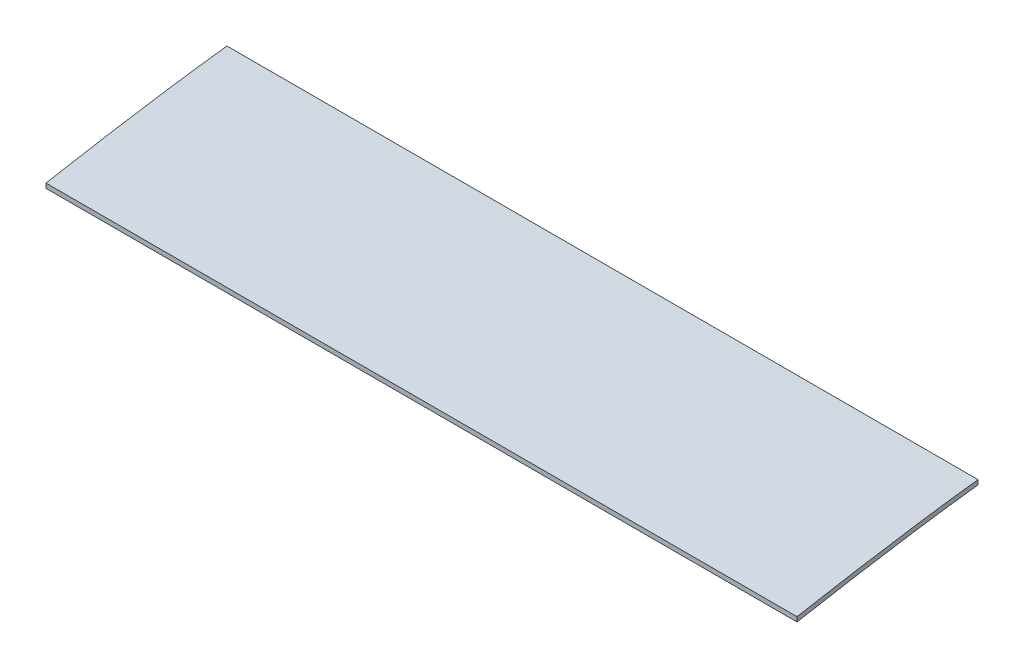
SolidWorks part; units mm, degrees
material "Balsa"
ref_plane "Front" through (0, 0, 0) normal (0, 0, 1) x (1, 0, 0)
ref_plane "Top" through (0, 0, 0) normal (0, 1, 0) x (1, 0, 0)
ref_plane "Right" through (0, 0, 0) normal (1, 0, 0) x (0, 0, -1)
sketch "Sketch1" plane through (0, 0, 0) normal (1, 0, 0) x (0, 0, -1)
  line L0 (485.9211, -48.8296) -> (485.9211, -45.6021)
  line L1 (612.9211, -29.0098) -> (612.9211, -25.8119)
  line L2 (612.9211, -14.3433) -> (612.9211, -28.6308) construction
  spline S0 degree 3 poles (7.7579, -2917.8825) (921.9308, -1.429) (846.8289, -45.9907) (789.3572, -23.4586) (777.0615, -18.6436) (760.5817, -13.0401) (739.9968, -7.1233) (715.5772, -0.3798) (687.647, 7.013) (656.6835, 14.9584) (623.1589, 23.2583) (587.5492, 31.6944) (550.3192, 40.0262) (511.9148, 48.0016) (472.7617, 55.3745) (433.2622, 61.9128) (393.7959, 67.4048) (354.7199, 71.6552) (316.357, 74.5357) (278.9313, 75.7536) (242.6994, 75.3938) (207.8706, 73.5467) (174.7468, 70.259) (143.6014, 65.7682) (114.7621, 60.1875) (88.5345, 53.6285) (65.199, 46.2382) (45.0006, 38.1339) (28.1586, 29.5092) (14.871, 20.5578) (6.1442, 12.3133) (1.9481, 6.1765) (0.6391, 3.0841) (0.217, 1.668) (-2.5675, -12.5382) (41.9664, -30.9514) (-2987.9583, 245.302) knots -0.191188 -0.191188 -0.191188 -0.191188 0.003802 0.014472 0.030564 0.051299 0.077028 0.107574 0.142399 0.180921 0.222525 0.266591 0.312515 0.35971 0.407632 0.455773 0.503669 0.550901 0.597096 0.641976 0.685512 0.727353 0.767354 0.805169 0.840471 0.872937 0.902335 0.928425 0.951113 0.970253 0.985871 0.993982 0.996753 0.997907 0.999293 1.048576 1.048576 1.048576 1.048576 only from (802.1511, -28.0117) to (0, 0) construction
  spline S1 degree 3 poles (802.1511, -28.0117) (801.1372, -27.7105) (797.2784, -26.5642) (789.3572, -23.4586) (777.0615, -18.6436) (760.5817, -13.0401) (739.9968, -7.1233) (715.5772, -0.3798) (687.647, 7.013) (656.6835, 14.9584) (623.1589, 23.2583) (587.5492, 31.6944) (550.3192, 40.0262) (511.9148, 48.0016) (472.7617, 55.3745) (433.2622, 61.9128) (393.7959, 67.4048) (354.7199, 71.6552) (316.357, 74.5357) (278.9313, 75.7536) (242.6994, 75.3938) (207.8706, 73.5467) (174.7468, 70.259) (143.6014, 65.7682) (114.7621, 60.1875) (88.5345, 53.6285) (65.199, 46.2382) (45.0006, 38.1339) (28.1586, 29.5092) (14.871, 20.5578) (6.1442, 12.3133) (1.9481, 6.1765) (0.6391, 3.0841) (0.217, 1.668) (0.0426, 0.7778) (0.0107, 0.1963) (0, 0) knots 0 0 0 0 0.003802 0.014472 0.030564 0.051299 0.077028 0.107574 0.142399 0.180921 0.222525 0.266591 0.312515 0.35971 0.407632 0.455773 0.503669 0.550901 0.597096 0.641976 0.685512 0.727353 0.767354 0.805169 0.840471 0.872937 0.902335 0.928425 0.951113 0.970253 0.985871 0.993982 0.996753 0.997907 0.999293 1 1 1 1 construction
  spline S2 degree 3 poles (-2990.4271, -217.8416) (65.0803, 52.4472) (-4.4846, 21.0798) (0.5702, -4.3968) (2.5361, -10.6164) (7.9982, -20.5501) (16.1137, -34.185) (25.7513, -48.9002) (36.932, -62.9388) (49.3364, -75.9186) (65.2269, -85.625) (84.4528, -91.7174) (106.8521, -96.1515) (132.5109, -98.5722) (161.1944, -99.0924) (192.7613, -97.7042) (227.0382, -94.5118) (263.8348, -89.6638) (302.9215, -83.3884) (344.0178, -75.9778) (386.7768, -67.7807) (430.7746, -59.2023) (475.4963, -50.6638) (520.3353, -42.6036) (564.5889, -35.4228) (607.4709, -29.4733) (648.1275, -25.0145) (685.6676, -22.1862) (719.1968, -21.0048) (747.8303, -21.2786) (770.6884, -22.8547) (787.0914, -25.0735) (864.3121, -38.8992) (925.0612, -103.9188) (1620.626, 2853.5132) knots -0.081662 -0.081662 -0.081662 -0.081662 0.001821 0.004613 0.009135 0.024676 0.044153 0.064937 0.086321 0.107138 0.1276 0.150893 0.177565 0.207668 0.241222 0.278203 0.318526 0.362031 0.408465 0.457479 0.508614 0.561296 0.614835 0.668438 0.721214 0.772202 0.820393 0.864766 0.904324 0.938132 0.965242 0.98469 0.99621 1.240504 1.240504 1.240504 1.240504 only from (0, 0) to (802.1511, -28.0117) construction
  spline S3 degree 3 poles (0, 0) (0.0175, -0.519) (0.0617, -1.8338) (0.5702, -4.3968) (2.5361, -10.6164) (7.9982, -20.5501) (16.1137, -34.185) (25.7513, -48.9002) (36.932, -62.9388) (49.3364, -75.9186) (65.2269, -85.625) (84.4528, -91.7174) (106.8521, -96.1515) (132.5109, -98.5722) (161.1944, -99.0924) (192.7613, -97.7042) (227.0382, -94.5118) (263.8348, -89.6638) (302.9215, -83.3884) (344.0178, -75.9778) (386.7768, -67.7807) (430.7746, -59.2023) (475.4963, -50.6638) (520.3353, -42.6036) (564.5889, -35.4228) (607.4709, -29.4733) (648.1275, -25.0145) (685.6676, -22.1862) (719.1968, -21.0048) (747.8303, -21.2786) (770.6884, -22.8547) (787.0914, -25.0735) (796.8423, -26.8193) (801.0977, -27.7751) (802.1511, -28.0117) knots 0 0 0 0 0.001821 0.004613 0.009135 0.024676 0.044153 0.064937 0.086321 0.107138 0.1276 0.150893 0.177565 0.207668 0.241222 0.278203 0.318526 0.362031 0.408465 0.457479 0.508614 0.561296 0.614835 0.668438 0.721214 0.772202 0.820393 0.864766 0.904324 0.938132 0.965242 0.98469 0.99621 1 1 1 1
  spline S4 degree 1 poles (3.1732, 0.1067) (802.8469, -24.9139) knots 0 0 1 1 construction
  spline S5 degree 3 poles (3.1732, 0.1067) (3.1819, -0.1521) (3.2011, -0.7036) (3.2467, -1.3257) (3.3354, -1.9569) (3.5122, -2.8621) (3.8204, -4.0789) (4.4162, -6.0041) (5.3425, -8.4272) (7.094, -12.2508) (9.7119, -17.0201) (13.0504, -22.7925) (16.4406, -28.4677) (21.0946, -35.9752) (27.1466, -45.1637) (33.7501, -53.8739) (39.4068, -60.5874) (43.8008, -65.4663) (48.3936, -70.0244) (54.8973, -75.4881) (64.0361, -81.1237) (76.0251, -85.8337) (88.754, -89.2337) (101.6501, -91.8371) (114.7087, -93.6633) (127.8778, -94.8443) (145.5183, -95.7216) (167.6295, -95.7019) (194.1715, -94.3241) (220.6668, -91.9192) (247.1006, -88.7182) (282.2622, -83.6318) (326.0721, -76.1243) (378.5138, -66.1663) (427.3837, -56.6179) (467.5708, -48.9466) (502.6305, -42.5412) (540.4526, -36.0194) (574.0029, -30.8794) (604.0597, -26.8599) (622.6663, -24.6152) (654.6275, -21.2837) (686.701, -18.8601) (722.4487, -17.8536) (749.311, -18.1454) (771.7414, -19.7555) (787.3336, -21.9396) (795.0967, -23.2791) (799.5629, -24.1765) (801.7493, -24.6674) (802.8469, -24.9139) knots 0 0 0 0 0.000977 0.001953 0.00293 0.003906 0.005859 0.007812 0.011719 0.015625 0.023437 0.03125 0.039062 0.046875 0.0625 0.078125 0.085937 0.09375 0.101562 0.109375 0.125 0.140625 0.15625 0.171875 0.1875 0.203125 0.21875 0.25 0.28125 0.3125 0.34375 0.375 0.4375 0.5 0.5625 0.612294 0.643544 0.6875 0.746862 0.762487 0.793737 0.8125 0.875 0.90625 0.9375 0.96875 0.984375 0.992187 0.996094 1 1 1 1
  dimension "D2" = 127
  dimension "D1" = 3.175
extrude "Boss-Extrude1" add sketch "Sketch1" along normal up to surface (263.525 mm away) and the other way up to surface (263.525 mm away) contours S5 L0 S3 L1
